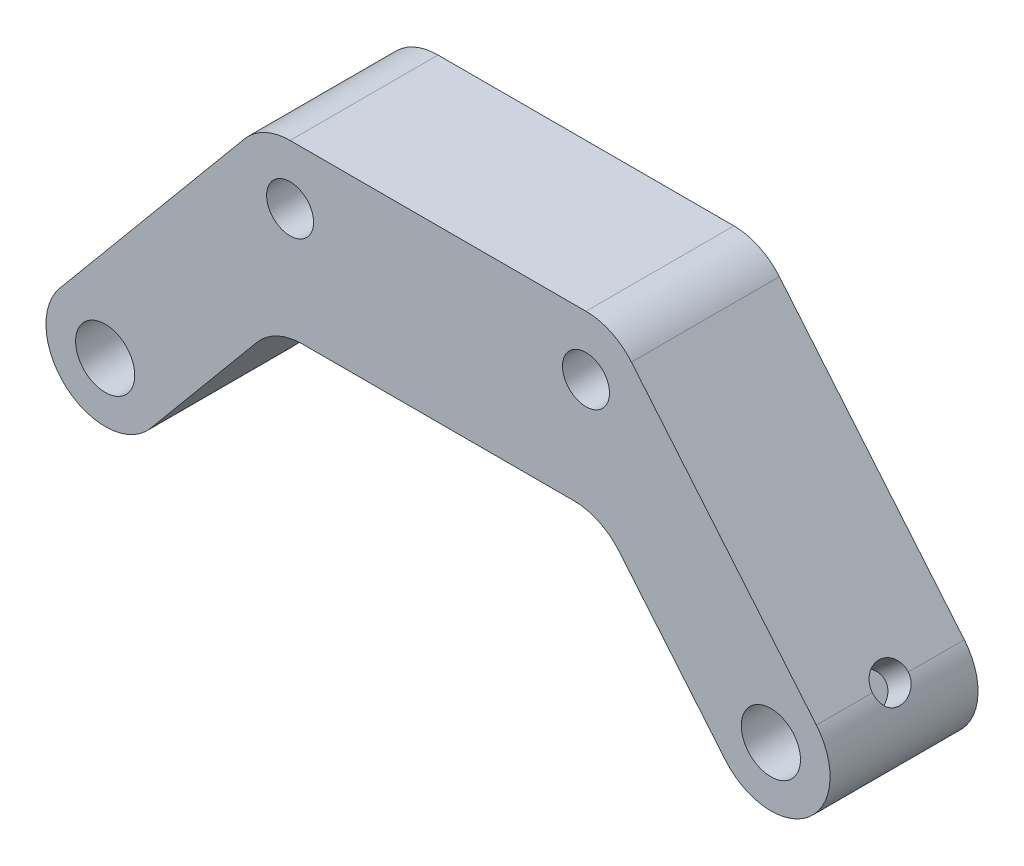
SolidWorks part; units mm, degrees
ref_plane "Front Plane" through (0, 0, 0) normal (0, 0, 1) x (1, 0, 0)
ref_plane "Top Plane" through (0, 0, 0) normal (0, 1, 0) x (1, 0, 0)
ref_plane "Right Plane" through (0, 0, 0) normal (1, 0, 0) x (0, 0, -1)
sketch "Sketch1" plane through (0, 0, 0) normal (0, 0, 1) x (1, 0, 0)
  line L3 (77.8065, 25) -> (-13.755, 25) construction
  line L4 (0, 0) -> (-37, 0) construction
  line L5 (-26.1458, 35.1215) -> (-51.1458, 5.1215)
  line L6 (0, 0) -> (0, 46.3802) construction
  line L7 (18.3393, 15) -> (-18.3393, 15)
  line L8 (-24.4851, 12.1215) -> (-38.8542, -5.1215)
  line L9 (-20, 38) -> (20, 38)
  line L10 (-26.245, 25) -> (-131.3577, 25) construction
  line L11 (-41, 0) -> (-110.6355, 0) construction
  line L12 (24.4851, 12.1215) -> (38.8542, -5.1215)
  line L13 (26.1458, 35.1215) -> (51.1458, 5.1215)
  circle A1 centre (-45, 0) radius 4 construction
  arc A6 (-51.1458, 5.1215) -> (-38.8542, -5.1215) centre (-45, 0) ccw
  circle A7 centre (-20, 30) radius 3.175 construction
  arc A8 (-20, 38) -> (-26.1458, 35.1215) centre (-20, 30) ccw
  arc A9 (51.1458, 5.1215) -> (38.8542, -5.1215) centre (45, 0) cw
  arc A10 (20, 38) -> (26.1458, 35.1215) centre (20, 30) cw
  circle A11 centre (45, 0) radius 4 construction
  circle A12 centre (20, 30) radius 3.175 construction
  arc A13 (-18.3393, 15) -> (-24.4851, 12.1215) centre (-18.3393, 7) ccw
  arc A14 (24.4851, 12.1215) -> (18.3393, 15) centre (18.3393, 7) ccw
  point P26 (0, 15)
  point P29 (0, 38)
  point P33 (-22.0863, 15)
  point P36 (22.0863, 15)
  dimension "D1" = 25
  dimension "D2" = 8
  dimension "D4" = 16
  dimension "D5" = 6.35
  dimension "D6" = 16
  dimension "D10" = 8
  dimension "D3" = 45
  dimension "D7" = 5
  dimension "D8" = 20
  dimension "D9" = 10
  dimension "D11" = 45
extrude "Boss-Extrude1" add sketch "Sketch1" along normal blind 20
sketch "Sketch2" plane through (0, 0, 20) normal (0, 0, 1) x (1, 0, 0)
  circle A0 centre (-45, 0) radius 4
  circle A1 centre (44.9959, 0) radius 4
extrude "Cut-Extrude1" cut sketch "Sketch2" against normal blind 15
sketch "Sketch4" plane through (0, 0, 20) normal (0, 0, 1) x (1, 0, 0)
  line L0 (0, 46.3802) -> (0, 25) construction
  line L1 (-13.5842, 30) -> (-16.7921, 35.5562) construction
  line L2 (-16.7921, 35.5562) -> (-23.2079, 35.5562) construction
  line L3 (-23.2079, 35.5562) -> (-26.4158, 30) construction
  line L4 (-26.4158, 30) -> (-23.2079, 24.4437) construction
  line L5 (-23.2079, 24.4437) -> (-16.7921, 24.4437) construction
  line L6 (-16.7921, 24.4437) -> (-13.5842, 30) construction
  line L7 (77.8065, 25) -> (-13.755, 25) construction
  line L8 (0, 0) -> (0, 46.3802) construction
  circle A0 centre (-20, 30) radius 7.3025
  circle A1 centre (20, 30) radius 7.3025
  dimension "D2" = 14.605
  dimension "D1" = 12.8316
ref_plane "Plane1" through (0, 0, 10) normal (0, 0, -1) x (-1, 0, 0)
sketch "Sketch6" plane through (-32.7031, 27.2526, 0) normal (-0.7682, 0.6402, 0) x (0, 0, 1)
  line L0 (20, -28.8083) -> (0, -28.8083) construction
  circle A0 centre (10, -28.8083) radius 2.425
  dimension "D1" = 4.85
extrude "Cut-Extrude5" cut sketch "Sketch6" against normal blind 6
mirror "Mirror2" about plane through (0, 0, 0) normal (1, 0, 0) of "Cut-Extrude5"
sketch "Sketch7" plane through (0, 0, 20) normal (0, 0, 1) x (1, 0, 0)
  circle A0 centre (-20, 30) radius 3.175
  circle A1 centre (20, 30) radius 3.175
extrude "Cut-Extrude6" cut sketch "Sketch7" against normal up to next
